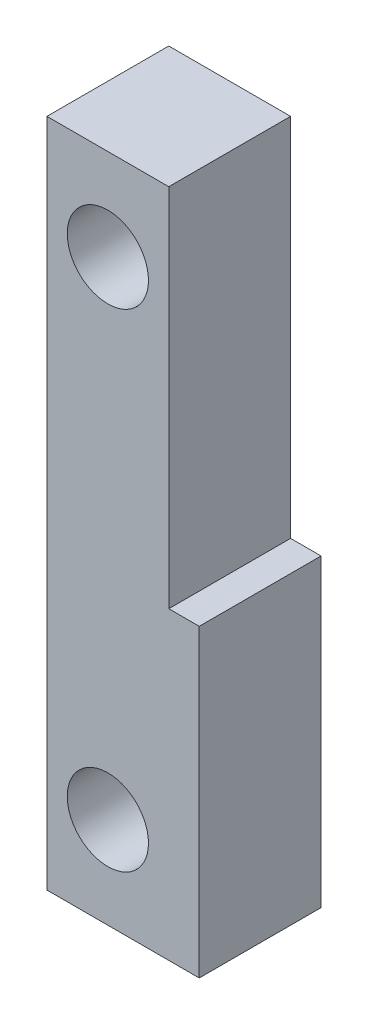
SolidWorks part; units mm, degrees
ref_plane "Front Plane" through (0, 0, 0) normal (0, 0, 1) x (1, 0, 0)
ref_plane "Top Plane" through (0, 0, 0) normal (0, 1, 0) x (1, 0, 0)
ref_plane "Right Plane" through (0, 0, 0) normal (1, 0, 0) x (0, 0, -1)
sketch "Sketch1" plane through (0, 0, 0) normal (0, 1, 0) x (1, 0, 0)
  line L1 (-3, 3) -> (3, 3)
  line L2 (-3, 3) -> (-3, -3)
  line L3 (-3, -3) -> (3, -3)
  line L4 (3, 3) -> (3, -3)
  line L5 (-3, 3) -> (3, -3) construction
  line L6 (-3, -3) -> (3, 3) construction
  point P0 (0, 0)
  dimension "D1" = 6
  dimension "D2" = 6
extrude "Boss-Extrude1" add sketch "Sketch1" along normal blind 33
sketch "Sketch2" plane through (0, 0, 3) normal (0, 0, 1) x (1, 0, 0)
  line L0 (0, 33) -> (0, 0) construction
  line L1 (-3, 33) -> (3, 33) construction
  circle A0 centre (0, 28.5) radius 2
  circle A1 centre (0, 4.5) radius 2
  dimension "D3" = 4
  dimension "D4" = 4
  dimension "D1" = 4.5
  dimension "D2" = 4.5
extrude "Cut-Extrude1" cut sketch "Sketch2" against normal blind 33
sketch "Sketch3" plane through (3, 0, 0) normal (1, 0, 0) x (0, 0, -1)
  line L0 (3, 33) -> (3, 0) construction
  line L1 (-3, 0) -> (3, 0)
  line L2 (-3, 0) -> (-3, 15)
  line L3 (-3, 15) -> (3, 15)
  line L4 (3, 0) -> (3, 15)
  dimension "D1" = 15
extrude "Boss-Extrude2" add sketch "Sketch3" along normal blind 1.5
